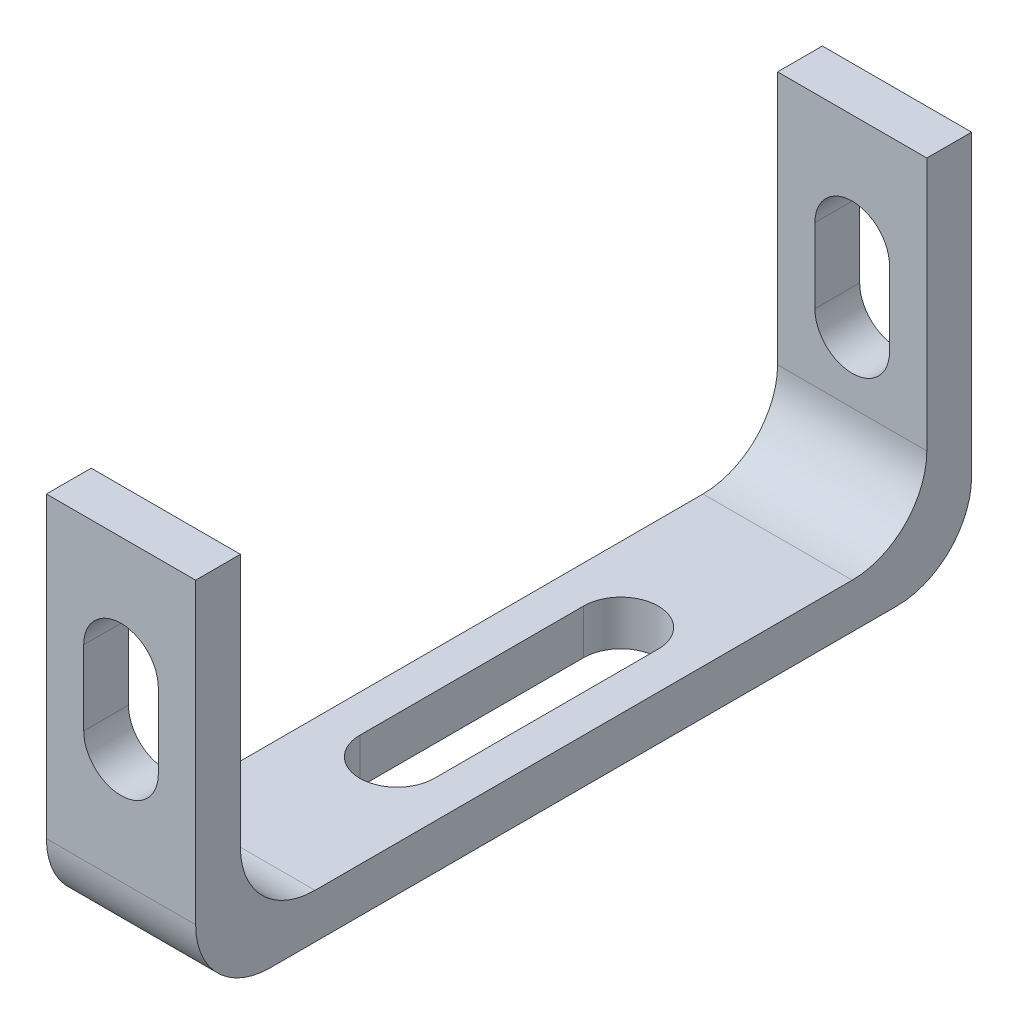
SolidWorks part; units mm, degrees
material "AISI 304"
ref_plane "前视基准面" through (0, 0, 0) normal (0, 0, 1) x (1, 0, 0)
ref_plane "上视基准面" through (0, 0, 0) normal (0, 1, 0) x (1, 0, 0)
ref_plane "右视基准面" through (0, 0, 0) normal (1, 0, 0) x (0, 0, -1)
sketch "草图1" plane through (0, 0, 0) normal (1, 0, 0) x (0, 0, -1)
  line L0 (0, 0) -> (52, 0)
  line L1 (52, 0) -> (52, 25)
  line L2 (0, 25) -> (0, 0)
  line L3 (3, 25) -> (3, 3)
  line L4 (3, 3) -> (49, 3)
  line L5 (49, 3) -> (49, 25)
  line L6 (0, 25) -> (3, 25)
  line L7 (49, 25) -> (52, 25)
  dimension "D1" = 52
  dimension "D2" = 25
  dimension "D3" = 25
  dimension "D4" = 3
extrude "凸台-拉伸1" add sketch "草图1" along normal blind 10
fillet "圆角1" radius 5 4 edges at (5, 0, 0) (5, 0, -52) (5, 3, -3) (5, 3, -49)
sketch "草图2" plane through (0, 3, 0) normal (0, 1, 0) x (1, 0, 0)
  line L0 (5, 44) -> (5, 8) construction
  line L1 (10, 44) -> (0, 44) construction
  line L2 (0, 8) -> (10, 8) construction
  line L3 (5, 33.5) -> (5, 18.5) construction
  line L4 (7.5, 33.5) -> (7.5, 18.5)
  line L5 (2.5, 33.5) -> (2.5, 18.5)
  arc A0 (7.5, 33.5) -> (2.5, 33.5) centre (5, 33.5) ccw
  arc A1 (2.5, 18.5) -> (7.5, 18.5) centre (5, 18.5) ccw
  point P8 (5, 26)
  dimension "D2" = 2.5
  dimension "D1" = 15
extrude "切除-拉伸1" cut sketch "草图2" against normal through all
sketch "草图3" plane through (0, 0, 0) normal (0, 0, 1) x (1, 0, 0)
  line L0 (5, 25) -> (5, 5) construction
  line L1 (10, 25) -> (0, 25) construction
  line L2 (0, 5) -> (10, 5) construction
  line L3 (5, 17.5) -> (5, 12.5) construction
  line L7 (7.5, 17.5) -> (7.5, 12.5)
  line L8 (2.5, 17.5) -> (2.5, 12.5)
  line L9 (10, 0) -> (0, 0) construction
  arc A2 (7.5, 17.5) -> (2.5, 17.5) centre (5, 17.5) ccw
  arc A3 (2.5, 12.5) -> (7.5, 12.5) centre (5, 12.5) ccw
  point P8 (5, 15)
  dimension "D3" = 2.5
  dimension "D1" = 15
  dimension "D2" = 5
extrude "切除-拉伸2" cut sketch "草图3" against normal through all
